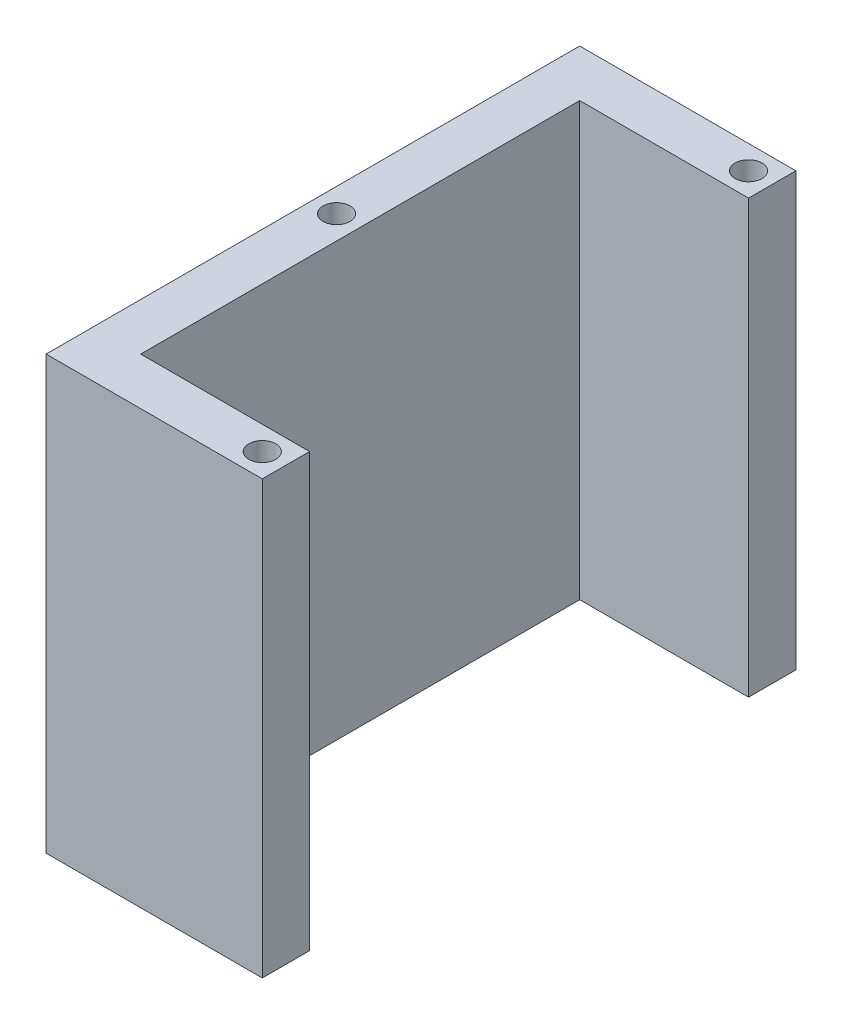
SolidWorks part; units mm, degrees
ref_plane "Front Plane" through (0, 0, 0) normal (0, 0, 1) x (1, 0, 0)
ref_plane "Top Plane" through (0, 0, 0) normal (0, 1, 0) x (1, 0, 0)
ref_plane "Right Plane" through (0, 0, 0) normal (1, 0, 0) x (0, 0, -1)
sketch "Sketch1" plane through (0, 0, 0) normal (0, 1, 0) x (1, 0, 0)
  line L0 (-19.5, -39.5) -> (-19.5, 39.5)
  line L1 (-12.5, -32.5) -> (12.5, -32.5)
  line L2 (-12.5, -32.5) -> (-12.5, 32.5)
  line L3 (-12.5, 32.5) -> (12.5, 32.5)
  line L4 (12.5, -32.5) -> (12.5, 32.5)
  line L5 (-12.5, -32.5) -> (12.5, 32.5) construction
  line L6 (-12.5, 32.5) -> (12.5, -32.5) construction
  line L7 (-19.5, 39.5) -> (19.5, 39.5)
  line L8 (19.5, -39.5) -> (19.5, 39.5)
  line L9 (-19.5, -39.5) -> (19.5, -39.5)
  line L10 (12.5, 32.5) -> (12.5, 39.5)
  line L11 (12.5, -32.5) -> (12.5, -39.5)
  point P0 (0, 0)
  dimension "D1" = 25
  dimension "D2" = 65
  dimension "D3" = 7
extrude "Boss-Extrude1" add sketch "Sketch1" along normal blind 64 contours L11 L1 L2 L3 L10 L7 L0 L9
sketch "Sketch2" plane through (0, 0, 0) normal (0, 1, 0) x (1, 0, 0)
  line L0 (-11.4176, 39.5) -> (-11.4176, 36) construction
  line L1 (-19.5, 39.5) -> (12.5, 39.5) construction
  line L2 (-19.5, 36) -> (-16, 36) construction
  line L3 (-19.5, -39.5) -> (-19.5, 39.5) construction
  line L4 (-17.6, 0) -> (17.6, 0) construction
  line L5 (0, 0) -> (-8.3459, 0) construction
  line L6 (12.5, 36) -> (9, 36) construction
  line L7 (12.5, 32.5) -> (12.5, 39.5) construction
  circle A0 centre (-16, 36) radius 2
  circle A1 centre (-16, -36) radius 2
  circle A2 centre (9, 36) radius 2
  circle A3 centre (9, -36) radius 2
extrude "Cut-Extrude1" cut sketch "Sketch2" along normal blind 5.7
ref_plane "Plane1" through (0, 64, 0) normal (0, 1, 0) x (1, 0, 0)
sketch "Sketch3" plane through (0, 64, 0) normal (0, 1, 0) x (1, 0, 0)
  line L0 (-19.5, 0) -> (-16, 0) construction
  line L1 (-19.5, -39.5) -> (-19.5, 39.5) construction
  line L2 (12.5, -36) -> (9, -36) construction
  line L3 (12.5, -32.5) -> (12.5, -39.5) construction
  circle A0 centre (-16, 0) radius 2
  circle A1 centre (9, -36) radius 2
  circle A2 centre (9, 36) radius 2
extrude "Cut-Extrude2" cut sketch "Sketch3" against normal blind 5.7
